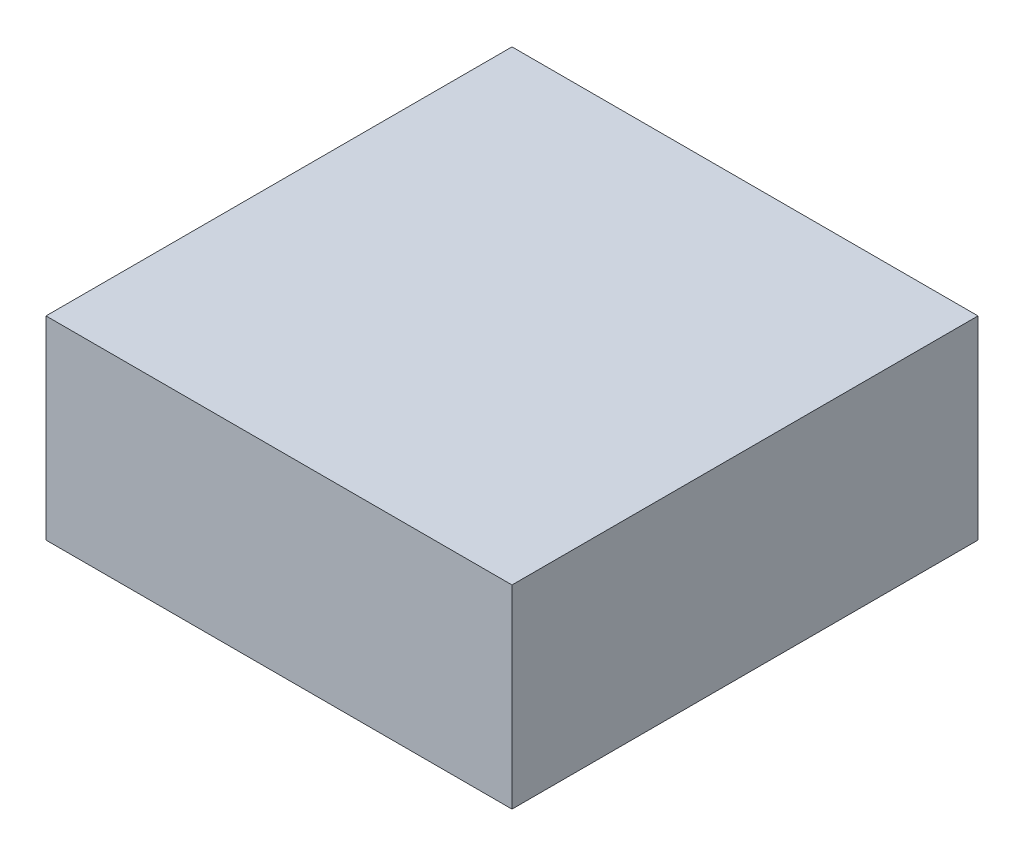
SolidWorks part; units mm, degrees
material "1100-H16 Rod (SS)"
ref_plane "Front Plane" through (0, 0, 0) normal (0, 0, 1) x (1, 0, 0)
ref_plane "Top Plane" through (0, 0, 0) normal (0, 1, 0) x (1, 0, 0)
ref_plane "Right Plane" through (0, 0, 0) normal (1, 0, 0) x (0, 0, -1)
sketch "Sketch1" plane through (0, 0, 0) normal (0, 1, 0) x (1, 0, 0)
  line L1 (-19.05, -19.05) -> (19.05, -19.05)
  line L2 (-19.05, -19.05) -> (-19.05, 19.05)
  line L3 (-19.05, 19.05) -> (19.05, 19.05)
  line L4 (19.05, -19.05) -> (19.05, 19.05)
  line L5 (-19.05, -19.05) -> (19.05, 19.05) construction
  line L6 (-19.05, 19.05) -> (19.05, -19.05) construction
  point P0 (0, 0)
  dimension "D1" = 38.1
  dimension "D2" = 38.1
extrude "Boss-Extrude1" add sketch "Sketch1" along normal blind 15.875
